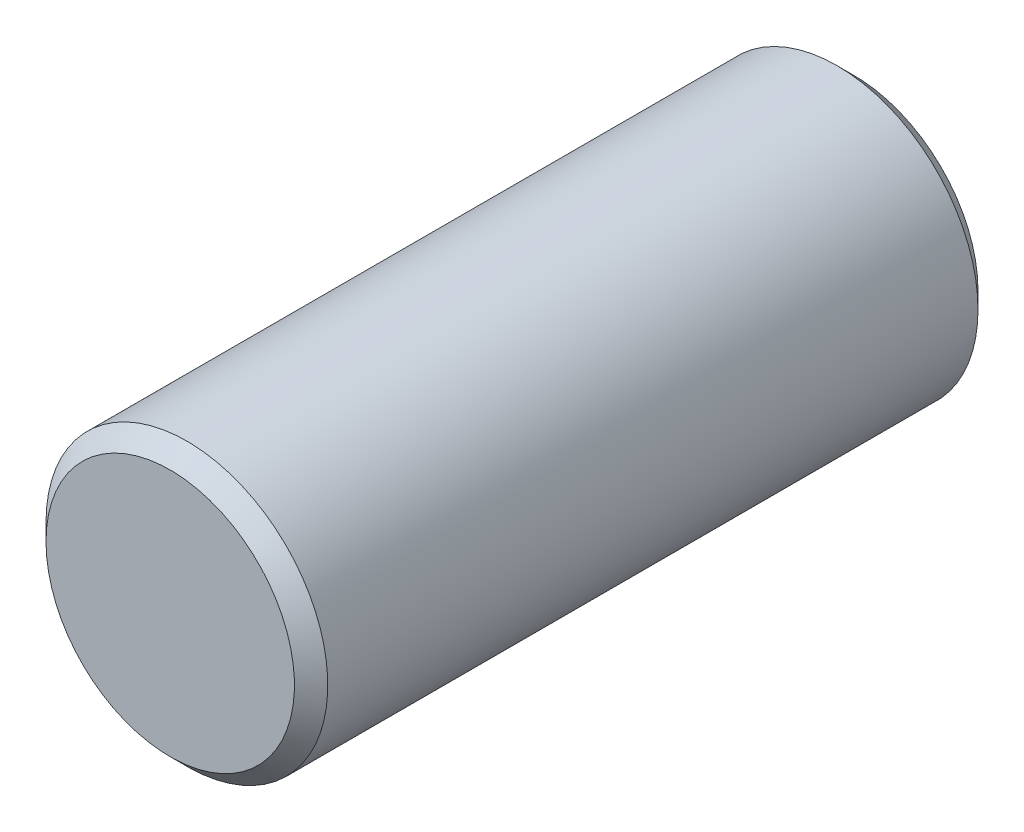
SolidWorks part; units mm, degrees
ref_plane "Front Plane" through (0, 0, 0) normal (0, 0, 1) x (1, 0, 0)
ref_plane "Top Plane" through (0, 0, 0) normal (0, 1, 0) x (1, 0, 0)
ref_plane "Right Plane" through (0, 0, 0) normal (1, 0, 0) x (0, 0, -1)
sketch "Sketch1" plane through (0, 0, 0) normal (0, 0, 1) x (1, 0, 0)
  circle A0 centre (0, 0) radius 429.26
  dimension "D1" = 858.52
extrude "Boss-Extrude1" add sketch "Sketch1" along normal mid plane 2082.8
chamfer "Chamfer1" distance 50.8 angle 45 2 edges at (429.26, 0, -1041.4) (429.26, 0, 1041.4)
